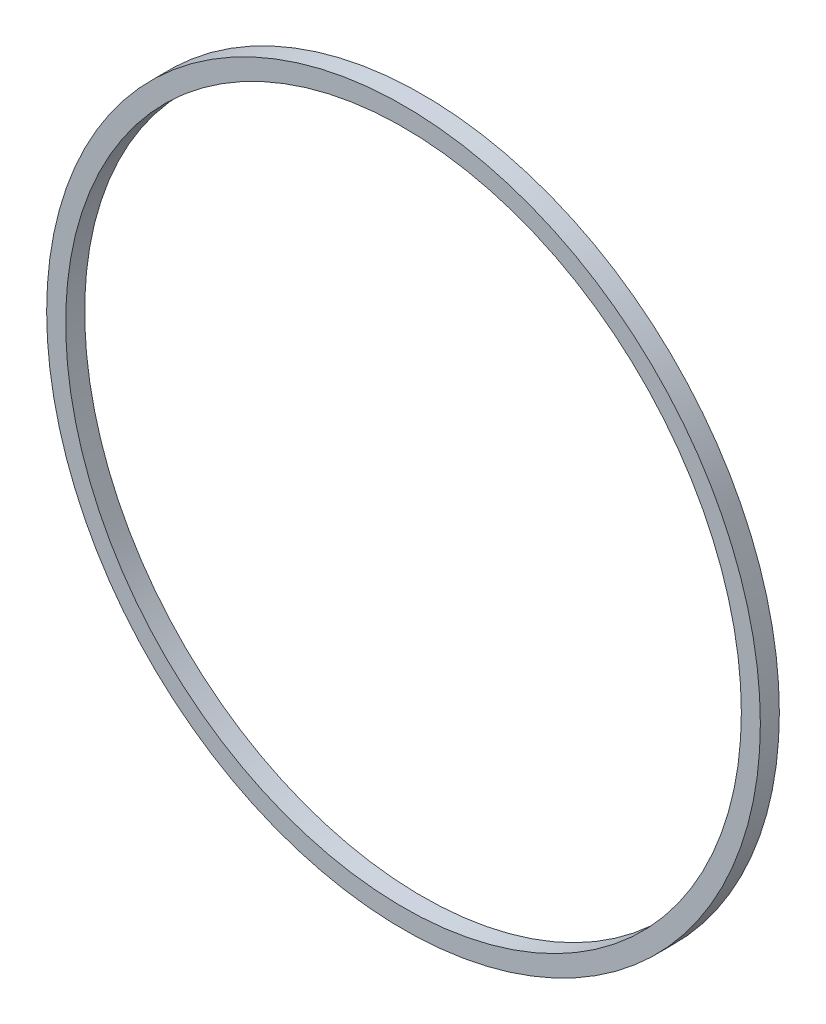
SolidWorks part; units mm, degrees
ref_plane "Alzado" through (0, 0, 0) normal (0, 0, 1) x (1, 0, 0)
ref_plane "Planta" through (0, 0, 0) normal (0, 1, 0) x (1, 0, 0)
ref_plane "Vista lateral" through (0, 0, 0) normal (1, 0, 0) x (0, 0, -1)
sketch "Croquis1" plane through (0, 0, 0) normal (0, 0, 1) x (1, 0, 0)
  circle A0 centre (0, 0) radius 40
  circle A1 centre (0, 0) radius 42.25
  dimension "D1" = 80
  dimension "D2" = 2.25
extrude "Saliente-Extruir1" add sketch "Croquis1" along normal blind 2.25
